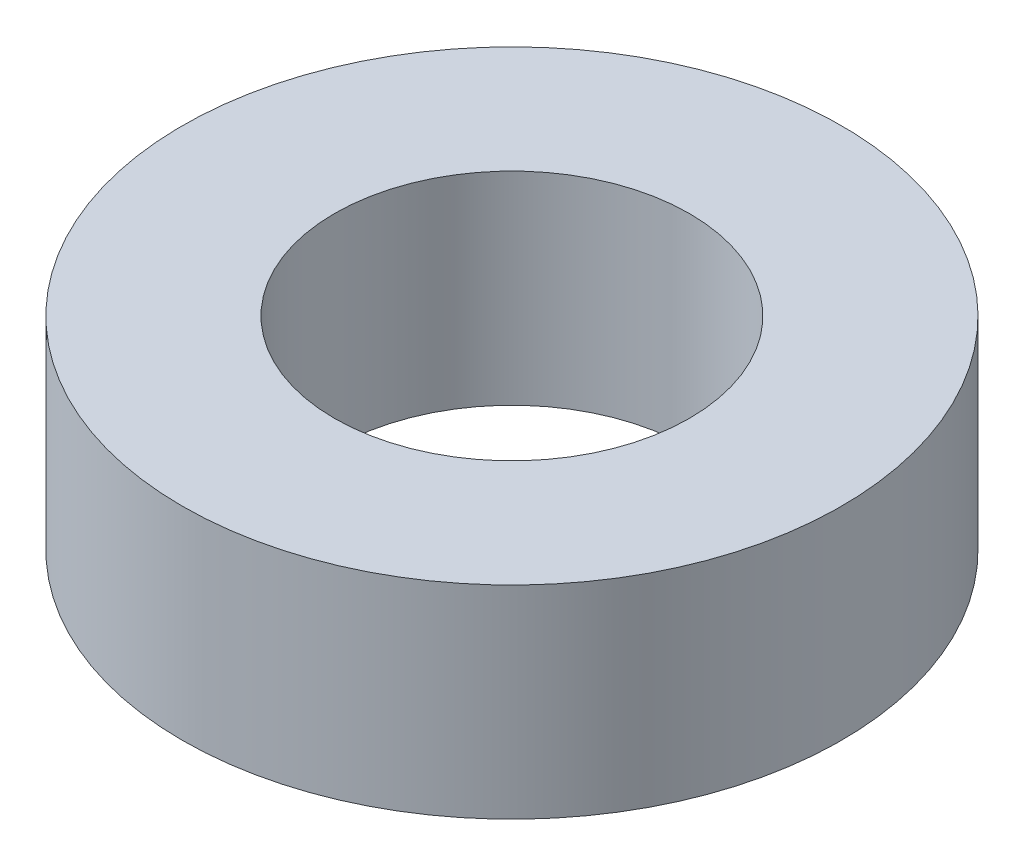
SolidWorks part; units mm, degrees
ref_plane "Ön Düzlem" through (0, 0, 0) normal (0, 0, 1) x (1, 0, 0)
ref_plane "Üst Düzlem" through (0, 0, 0) normal (0, 1, 0) x (1, 0, 0)
ref_plane "Sağ Düzlem" through (0, 0, 0) normal (1, 0, 0) x (0, 0, -1)
sketch "Sketch1" plane through (0, 0, 0) normal (0, 1, 0) x (1, 0, 0)
  circle A0 centre (0, 0) radius 6.5
  circle A1 centre (0, 0) radius 3.5
  dimension "D1" = 7
  dimension "D2" = 13
extrude "Boss-Extrude1" add sketch "Sketch1" along normal blind 4
